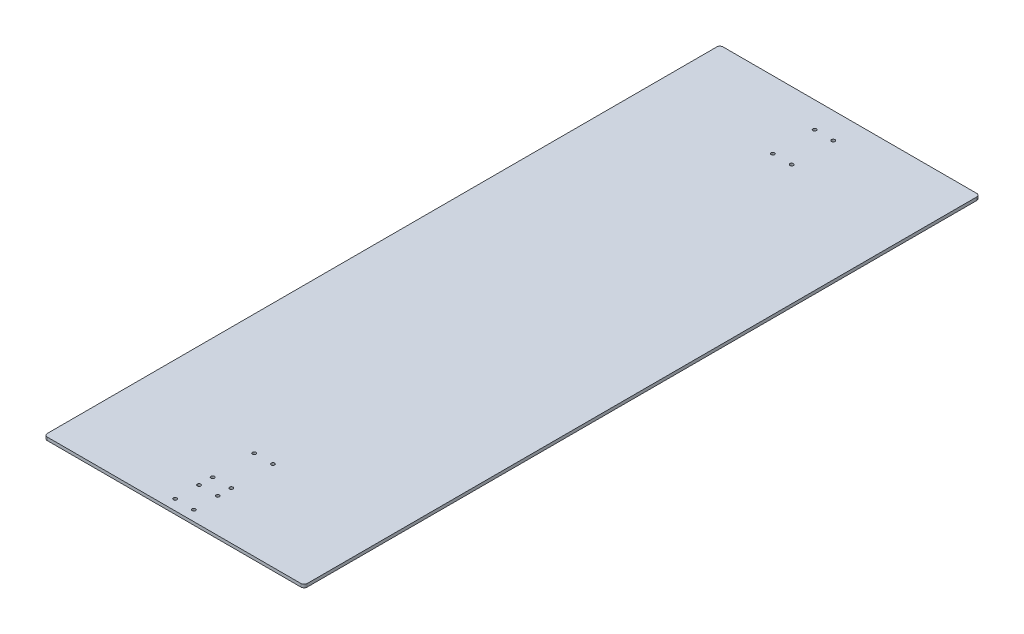
SolidWorks part; units mm, degrees
ref_plane "前视基准面" through (0, 0, 0) normal (0, 0, 1) x (1, 0, 0)
ref_plane "上视基准面" through (0, 0, 0) normal (0, 1, 0) x (1, 0, 0)
ref_plane "右视基准面" through (0, 0, 0) normal (1, 0, 0) x (0, 0, -1)
sketch "草图1" plane through (0, 0, 0) normal (0, 1, 0) x (1, 0, 0)
  line L1 (-125, -325) -> (125, -325)
  line L2 (-125, -325) -> (-125, 325)
  line L3 (-125, 325) -> (125, 325)
  line L4 (125, -325) -> (125, 325)
  line L5 (-125, -325) -> (125, 325) construction
  line L6 (-125, 325) -> (125, -325) construction
  point P0 (0, 0)
  dimension "D1" = 650
  dimension "D2" = 250
extrude "凸台-拉伸1" add sketch "草图1" along normal blind 3
sketch "草图2" plane through (0, 3, 0) normal (0, 1, 0) x (1, 0, 0)
  line L0 (-197.9745, 300) -> (197.9745, 300) construction
  line L1 (125, 325) -> (-125, 325) construction
  line L2 (125, -325) -> (125, 325) construction
  line L3 (-125, 325) -> (-125, -325) construction
  line L4 (-197.9745, -250) -> (278.6421, -250) construction
  line L5 (105, 300) -> (105, -289.6245) construction
  line L6 (-105, 300) -> (-105, -357.5754) construction
  circle A0 centre (105, 300) radius 1.65
  circle A1 centre (-105, 300) radius 1.65
  circle A2 centre (70, 300) radius 1.65
  circle A3 centre (-70, 300) radius 1.65
  circle A4 centre (105, -250) radius 1.65
  circle A5 centre (70, -250) radius 1.65
  circle A6 centre (-105, -250) radius 1.65
  circle A7 centre (-70, -250) radius 1.65
  dimension "D2" = 3.3
  dimension "D3" = 3.3
  dimension "D4" = 20
  dimension "D5" = 20
  dimension "D6" = 3.3
  dimension "D7" = 3.3
  dimension "D8" = 35
  dimension "D9" = 35
  dimension "D11" = 3.3
  dimension "D12" = 3.3
  dimension "D13" = 35
  dimension "D14" = 3.3
  dimension "D15" = 3.3
  dimension "D16" = 35
  dimension "D1" = 25
  dimension "D10" = 550
extrude "切除-拉伸1" [suppressed] cut sketch "草图2" against normal blind 10
sketch "草图3" plane through (0, 3, 0) normal (0, 1, 0) x (1, 0, 0)
  line L0 (-224.8383, -279) -> (320.6135, -279) construction
  line L1 (-125, -325) -> (125, -325) construction
  line L2 (0, -125.267) -> (0, -357.6972) construction
  line L3 (-256.3451, -239) -> (301.8238, -239) construction
  line L4 (-199.0693, 300) -> (230.008, 300) construction
  line L5 (125, 325) -> (-125, 325) construction
  line L6 (-174.069, 260) -> (205.6196, 260) construction
  circle A0 centre (9, -279) radius 1.65
  circle A1 centre (-9, -279) radius 1.65
  circle A2 centre (9, -239) radius 1.65
  circle A3 centre (-9, -239) radius 1.65
  circle A4 centre (9, 300) radius 1.65
  circle A5 centre (-9, 300) radius 1.65
  circle A6 centre (9, 260) radius 1.65
  circle A7 centre (-9, 260) radius 1.65
  point P31 (12.3873, 260)
  dimension "D2" = 18
  dimension "D4" = 3.3
  dimension "D5" = 3.3
  dimension "D7" = 3.3
  dimension "D8" = 3.3
  dimension "D9" = 9
  dimension "D10" = 9
  dimension "D12" = 9
  dimension "D13" = 9
  dimension "D14" = 3.3
  dimension "D15" = 3.3
  dimension "D17" = 18
  dimension "D18" = 9
  dimension "D19" = 3.3
  dimension "D20" = 3.3
  dimension "D1" = 46
  dimension "D3" = 9
  dimension "D6" = 86
  dimension "D11" = 25
  dimension "D16" = 65
extrude "切除-拉伸2" cut sketch "草图3" against normal blind 10
sketch "草图4" plane through (0, 3, 0) normal (0, 1, 0) x (1, 0, 0)
  line L0 (0, 122.3471) -> (0, -356.5293) construction
  line L1 (-173.4467, -292) -> (210.8224, -292) construction
  line L2 (-125, -325) -> (125, -325) construction
  line L3 (-160.5988, -315) -> (226.0063, -315) construction
  circle A0 centre (9, -292) radius 1.65
  circle A1 centre (-9, -292) radius 1.65
  circle A2 centre (-9, -315) radius 1.65
  circle A3 centre (9, -315) radius 1.65
  point P17 (9.8176, -292)
  point P18 (10.61, -315)
  dimension "D3" = 18
  dimension "D4" = 18
  dimension "D5" = 9
  dimension "D6" = 9
  dimension "D7" = 3.3
  dimension "D8" = 3.3
  dimension "D9" = 3.3
  dimension "D10" = 3.3
  dimension "D1" = 33
  dimension "D2" = 10
extrude "切除-拉伸3" cut sketch "草图4" against normal blind 3
fillet "圆角1" radius 3 4 edges at (125, 1.5, -325) (-125, 1.5, -325) (-125, 1.5, 325) (125, 1.5, 325)
